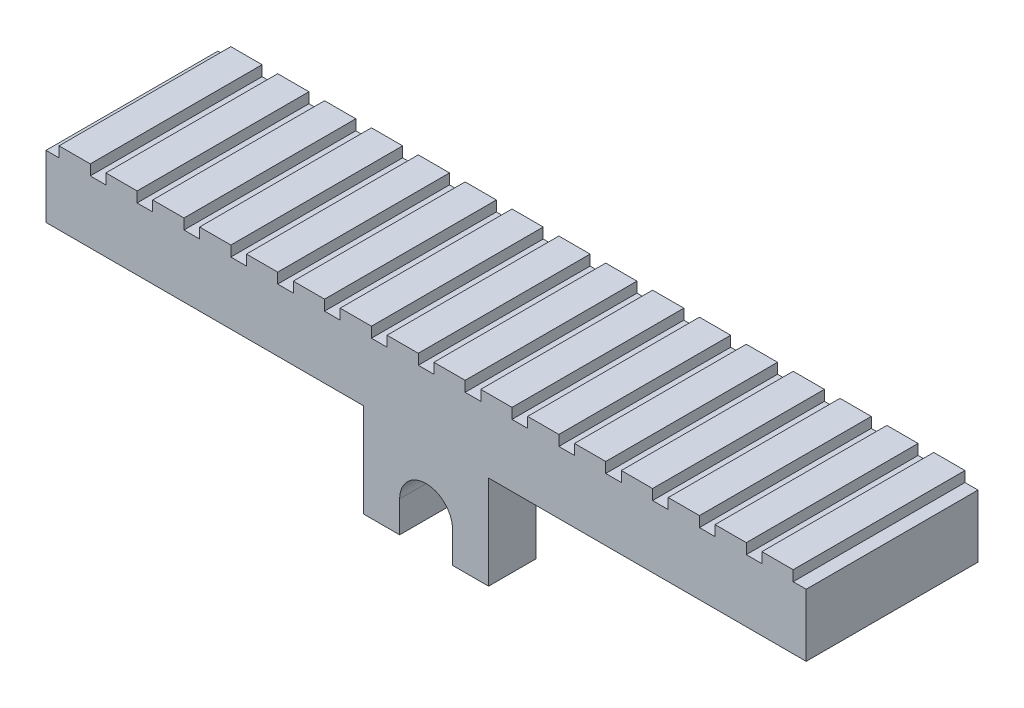
SolidWorks part; units mm, degrees
material "6061-T6 (SS)"
ref_plane "Front" through (0, 0, 0) normal (0, 0, 1) x (1, 0, 0)
ref_plane "Top" through (0, 0, 0) normal (0, 1, 0) x (1, 0, 0)
ref_plane "Right" through (0, 0, 0) normal (1, 0, 0) x (0, 0, -1)
sketch "Sketch4" plane through (0, 0, 0) normal (0, 1, 0) x (-1, 0, 0)
  line L2 (-36.5, 7.5) -> (36.5, 7.5)
  line L3 (-36.5, 7.5) -> (-36.5, -7.5)
  line L4 (-36.5, -7.5) -> (36.5, -7.5)
  line L5 (36.5, 7.5) -> (36.5, -7.5)
  point P1 (36.5, 0)
  point P2 (0, 7.5)
  dimension "D1" = 15
  dimension "D2" = 73
  dimension "D3" = 15
extrude "Boss-Extrude4" add sketch "Sketch4" against normal blind 6
sketch "Sketch15" plane through (0, 0, 0) normal (0, 1, 0) x (1, 0, 0)
  line L0 (0, 13.2788) -> (0, 21.5564) construction
  line L2 (0.75, 7.5) -> (3.75, 7.5)
  line L3 (0.75, 7.5) -> (0.75, -7.5)
  line L4 (0.75, -7.5) -> (3.75, -7.5)
  line L5 (3.75, 7.5) -> (3.75, -7.5)
  line L7 (5.25, 7.5) -> (8.25, 7.5)
  line L8 (5.25, 7.5) -> (5.25, -7.5)
  line L9 (5.25, -7.5) -> (8.25, -7.5)
  line L10 (8.25, 7.5) -> (8.25, -7.5)
  line L11 (9.75, 7.5) -> (12.75, 7.5)
  line L12 (9.75, 7.5) -> (9.75, -7.5)
  line L13 (9.75, -7.5) -> (12.75, -7.5)
  line L14 (12.75, 7.5) -> (12.75, -7.5)
  line L15 (14.25, 7.5) -> (17.25, 7.5)
  line L16 (14.25, 7.5) -> (14.25, -7.5)
  line L17 (14.25, -7.5) -> (17.25, -7.5)
  line L18 (17.25, 7.5) -> (17.25, -7.5)
  line L19 (18.75, 7.5) -> (21.75, 7.5)
  line L20 (18.75, 7.5) -> (18.75, -7.5)
  line L21 (18.75, -7.5) -> (21.75, -7.5)
  line L22 (21.75, 7.5) -> (21.75, -7.5)
  line L23 (23.25, 7.5) -> (26.25, 7.5)
  line L24 (23.25, 7.5) -> (23.25, -7.5)
  line L25 (23.25, -7.5) -> (26.25, -7.5)
  line L26 (26.25, 7.5) -> (26.25, -7.5)
  line L27 (27.75, 7.5) -> (30.75, 7.5)
  line L28 (27.75, 7.5) -> (27.75, -7.5)
  line L29 (27.75, -7.5) -> (30.75, -7.5)
  line L30 (30.75, 7.5) -> (30.75, -7.5)
  line L31 (32.25, 7.5) -> (35.25, 7.5)
  line L32 (32.25, 7.5) -> (32.25, -7.5)
  line L33 (32.25, -7.5) -> (35.25, -7.5)
  line L34 (35.25, 7.5) -> (35.25, -7.5)
  line L35 (-35.25, 7.5) -> (-35.25, -7.5)
  line L36 (-32.25, -7.5) -> (-35.25, -7.5)
  line L37 (-32.25, 7.5) -> (-32.25, -7.5)
  line L38 (-32.25, 7.5) -> (-35.25, 7.5)
  line L39 (-30.75, 7.5) -> (-30.75, -7.5)
  line L40 (-27.75, -7.5) -> (-30.75, -7.5)
  line L41 (-27.75, 7.5) -> (-27.75, -7.5)
  line L42 (-27.75, 7.5) -> (-30.75, 7.5)
  line L43 (-26.25, 7.5) -> (-26.25, -7.5)
  line L44 (-23.25, -7.5) -> (-26.25, -7.5)
  line L45 (-23.25, 7.5) -> (-23.25, -7.5)
  line L46 (-23.25, 7.5) -> (-26.25, 7.5)
  line L47 (-21.75, 7.5) -> (-21.75, -7.5)
  line L48 (-18.75, -7.5) -> (-21.75, -7.5)
  line L49 (-18.75, 7.5) -> (-18.75, -7.5)
  line L50 (-18.75, 7.5) -> (-21.75, 7.5)
  line L51 (-17.25, 7.5) -> (-17.25, -7.5)
  line L52 (-14.25, -7.5) -> (-17.25, -7.5)
  line L53 (-14.25, 7.5) -> (-14.25, -7.5)
  line L54 (-14.25, 7.5) -> (-17.25, 7.5)
  line L55 (-12.75, 7.5) -> (-12.75, -7.5)
  line L56 (-9.75, -7.5) -> (-12.75, -7.5)
  line L57 (-9.75, 7.5) -> (-9.75, -7.5)
  line L58 (-9.75, 7.5) -> (-12.75, 7.5)
  line L59 (-8.25, 7.5) -> (-8.25, -7.5)
  line L60 (-5.25, -7.5) -> (-8.25, -7.5)
  line L61 (-5.25, 7.5) -> (-5.25, -7.5)
  line L62 (-5.25, 7.5) -> (-8.25, 7.5)
  line L63 (-3.75, 7.5) -> (-3.75, -7.5)
  line L64 (-0.75, -7.5) -> (-3.75, -7.5)
  line L65 (-0.75, 7.5) -> (-0.75, -7.5)
  line L66 (-0.75, 7.5) -> (-3.75, 7.5)
  line L67 (36.5, 7.5) -> (-36.5, 7.5) construction
  line L68 (-36.5, -7.5) -> (36.5, -7.5) construction
  point P11 (2.25, 7.5)
  point P12 (-33.75, 7.5)
  point P13 (-29.25, 7.5)
  point P18 (6.75, 7.5)
  point P23 (11.25, 7.5)
  point P28 (15.75, 7.5)
  point P33 (20.25, 7.5)
  point P38 (24.75, 7.5)
  point P43 (29.25, 7.5)
  point P48 (33.75, 7.5)
  point P49 (-24.75, 7.5)
  point P50 (-20.25, 7.5)
  point P51 (-15.75, 7.5)
  point P52 (-11.25, 7.5)
  point P53 (-6.75, 7.5)
  point P54 (-2.25, 7.5)
  dimension "D1" = 3
  dimension "D2" = 4.5
  dimension "D4" = 4.5
  dimension "D3" = 8
extrude "Boss-Extrude6" add sketch "Sketch15" along normal blind 1
sketch "Sketch16" plane through (0, 0, 7.5) normal (0, 0, 1) x (1, 0, 0)
  line L68 (-35.25, 0) -> (-36.5, 0)
  line L69 (-36.5, 0) -> (-36.5, -6)
  line L70 (-36.5, -6) -> (36.5, -6)
  line L71 (36.5, -6) -> (36.5, 0)
  line L72 (36.5, 0) -> (35.25, 0)
  line L73 (35.25, 0) -> (35.25, 1)
  line L74 (35.25, 1) -> (32.25, 1)
  line L75 (32.25, 1) -> (32.25, 0)
  line L76 (32.25, 0) -> (30.75, 0)
  line L77 (30.75, 0) -> (30.75, 1)
  line L78 (30.75, 1) -> (27.75, 1)
  line L79 (27.75, 1) -> (27.75, 0)
  line L80 (27.75, 0) -> (26.25, 0)
  line L81 (26.25, 0) -> (26.25, 1)
  line L82 (26.25, 1) -> (23.25, 1)
  line L83 (23.25, 1) -> (23.25, 0)
  line L84 (23.25, 0) -> (21.75, 0)
  line L85 (21.75, 0) -> (21.75, 1)
  line L86 (21.75, 1) -> (18.75, 1)
  line L87 (18.75, 1) -> (18.75, 0)
  line L88 (18.75, 0) -> (17.25, 0)
  line L89 (17.25, 0) -> (17.25, 1)
  line L90 (17.25, 1) -> (14.25, 1)
  line L91 (14.25, 1) -> (14.25, 0)
  line L92 (14.25, 0) -> (12.75, 0)
  line L93 (12.75, 0) -> (12.75, 1)
  line L94 (12.75, 1) -> (9.75, 1)
  line L95 (9.75, 1) -> (9.75, 0)
  line L96 (9.75, 0) -> (8.25, 0)
  line L97 (8.25, 0) -> (8.25, 1)
  line L98 (8.25, 1) -> (5.25, 1)
  line L99 (5.25, 1) -> (5.25, 0)
  line L100 (5.25, 0) -> (3.75, 0)
  line L101 (3.75, 0) -> (3.75, 1)
  line L102 (3.75, 1) -> (0.75, 1)
  line L103 (0.75, 1) -> (0.75, 0)
  line L104 (0.75, 0) -> (-0.75, 0)
  line L105 (-0.75, 0) -> (-0.75, 1)
  line L106 (-0.75, 1) -> (-3.75, 1)
  line L107 (-3.75, 1) -> (-3.75, 0)
  line L108 (-3.75, 0) -> (-5.25, 0)
  line L109 (-5.25, 0) -> (-5.25, 1)
  line L110 (-5.25, 1) -> (-8.25, 1)
  line L111 (-8.25, 1) -> (-8.25, 0)
  line L112 (-8.25, 0) -> (-9.75, 0)
  line L113 (-9.75, 0) -> (-9.75, 1)
  line L114 (-9.75, 1) -> (-12.75, 1)
  line L115 (-12.75, 1) -> (-12.75, 0)
  line L116 (-12.75, 0) -> (-14.25, 0)
  line L117 (-14.25, 0) -> (-14.25, 1)
  line L118 (-14.25, 1) -> (-17.25, 1)
  line L119 (-17.25, 1) -> (-17.25, 0)
  line L120 (-17.25, 0) -> (-18.75, 0)
  line L121 (-18.75, 0) -> (-18.75, 1)
  line L122 (-18.75, 1) -> (-21.75, 1)
  line L123 (-21.75, 1) -> (-21.75, 0)
  line L124 (-21.75, 0) -> (-23.25, 0)
  line L125 (-23.25, 0) -> (-23.25, 1)
  line L126 (-23.25, 1) -> (-26.25, 1)
  line L127 (-26.25, 1) -> (-26.25, 0)
  line L128 (-26.25, 0) -> (-27.75, 0)
  line L129 (-27.75, 0) -> (-27.75, 1)
  line L130 (-27.75, 1) -> (-30.75, 1)
  line L131 (-30.75, 1) -> (-30.75, 0)
  line L132 (-30.75, 0) -> (-32.25, 0)
  line L133 (-32.25, 0) -> (-32.25, 1)
  line L134 (-32.25, 1) -> (-35.25, 1)
  line L135 (-35.25, 1) -> (-35.25, 0)
  line L136 (-35.25, 0) -> (-36.5, 0)
  line L137 (-36.5, 0) -> (-36.5, -6)
  line L138 (-36.5, -6) -> (36.5, -6)
  line L139 (36.5, -6) -> (36.5, 0)
  line L140 (36.5, 0) -> (35.25, 0)
  line L141 (35.25, 0) -> (35.25, 1)
  line L142 (35.25, 1) -> (32.25, 1)
  line L143 (32.25, 1) -> (32.25, 0)
  line L144 (32.25, 0) -> (30.75, 0)
  line L145 (30.75, 0) -> (30.75, 1)
  line L146 (30.75, 1) -> (27.75, 1)
  line L147 (27.75, 1) -> (27.75, 0)
  line L148 (27.75, 0) -> (26.25, 0)
  line L149 (26.25, 0) -> (26.25, 1)
  line L150 (26.25, 1) -> (23.25, 1)
  line L151 (23.25, 1) -> (23.25, 0)
  line L152 (23.25, 0) -> (21.75, 0)
  line L153 (21.75, 0) -> (21.75, 1)
  line L154 (21.75, 1) -> (18.75, 1)
  line L155 (18.75, 1) -> (18.75, 0)
  line L156 (18.75, 0) -> (17.25, 0)
  line L157 (17.25, 0) -> (17.25, 1)
  line L158 (17.25, 1) -> (14.25, 1)
  line L159 (14.25, 1) -> (14.25, 0)
  line L160 (14.25, 0) -> (12.75, 0)
  line L161 (12.75, 0) -> (12.75, 1)
  line L162 (12.75, 1) -> (9.75, 1)
  line L163 (9.75, 1) -> (9.75, 0)
  line L164 (9.75, 0) -> (8.25, 0)
  line L165 (8.25, 0) -> (8.25, 1)
  line L166 (8.25, 1) -> (5.25, 1)
  line L167 (5.25, 1) -> (5.25, 0)
  line L168 (5.25, 0) -> (3.75, 0)
  line L169 (3.75, 0) -> (3.75, 1)
  line L170 (3.75, 1) -> (0.75, 1)
  line L171 (0.75, 1) -> (0.75, 0)
  line L172 (0.75, 0) -> (-0.75, 0)
  line L173 (-0.75, 0) -> (-0.75, 1)
  line L174 (-0.75, 1) -> (-3.75, 1)
  line L175 (-3.75, 1) -> (-3.75, 0)
  line L176 (-3.75, 0) -> (-5.25, 0)
  line L177 (-5.25, 0) -> (-5.25, 1)
  line L178 (-5.25, 1) -> (-8.25, 1)
  line L179 (-8.25, 1) -> (-8.25, 0)
  line L180 (-8.25, 0) -> (-9.75, 0)
  line L181 (-9.75, 0) -> (-9.75, 1)
  line L182 (-9.75, 1) -> (-12.75, 1)
  line L183 (-12.75, 1) -> (-12.75, 0)
  line L184 (-12.75, 0) -> (-14.25, 0)
  line L185 (-14.25, 0) -> (-14.25, 1)
  line L186 (-14.25, 1) -> (-17.25, 1)
  line L187 (-17.25, 1) -> (-17.25, 0)
  line L188 (-17.25, 0) -> (-18.75, 0)
  line L189 (-18.75, 0) -> (-18.75, 1)
  line L190 (-18.75, 1) -> (-21.75, 1)
  line L191 (-21.75, 1) -> (-21.75, 0)
  line L192 (-21.75, 0) -> (-23.25, 0)
  line L193 (-23.25, 0) -> (-23.25, 1)
  line L194 (-23.25, 1) -> (-26.25, 1)
  line L195 (-26.25, 1) -> (-26.25, 0)
  line L196 (-26.25, 0) -> (-27.75, 0)
  line L197 (-27.75, 0) -> (-27.75, 1)
  line L198 (-27.75, 1) -> (-30.75, 1)
  line L199 (-30.75, 1) -> (-30.75, 0)
  line L200 (-30.75, 0) -> (-32.25, 0)
  line L201 (-32.25, 0) -> (-32.25, 1)
  line L202 (-32.25, 1) -> (-35.25, 1)
  line L203 (-35.25, 1) -> (-35.25, 0)
  dimension "D1" = 0
extrude "Boss-Extrude7" add sketch "Sketch16" along normal blind 1.5
sketch "Sketch21" plane through (0, 0, 9) normal (0, 0, 1) x (1, 0, 0)
  line L0 (0, -21.2656) -> (0, -26.6039) construction
  line L1 (-2.54, -12) -> (-2.54, -15)
  line L2 (-6, -6) -> (6, -6)
  line L3 (-6, -6) -> (-6, -15)
  line L4 (-6, -15) -> (-2.54, -15)
  line L5 (6, -6) -> (6, -15)
  line L6 (2.54, -12) -> (2.54, -15)
  line L7 (2.54, -15) -> (6, -15)
  line L10 (-36.5, -6) -> (36.5, -6) construction
  arc A0 (2.54, -12) -> (-2.54, -12) centre (0, -12) ccw
  point P6 (0, -6)
  dimension "D3" = 5.08
  dimension "D1" = 12
  dimension "D2" = 9
  dimension "D4" = 6
extrude "Boss-Extrude13" add sketch "Sketch21" against normal blind 7.715
sketch "Sketch22" plane through (0, -6, 0) normal (0, -1, 0) x (1, 0, 0)
  line L8 (-6, 1.285) -> (-6, 9) construction
  line L9 (-6, 7) -> (6, 7)
  line L10 (-6, 7) -> (-6, 3.285)
  line L11 (-6, 3.285) -> (6, 3.285)
  line L12 (6, 7) -> (6, 3.285)
  line L13 (6, 1.285) -> (6, 9) construction
  line L14 (-6, 9) -> (-2.54, 9) construction
  line L15 (-6, 1.285) -> (-2.54, 1.285) construction
  dimension "D1" = 2
  dimension "D3" = 2
extrude "Cut-Extrude2" cut sketch "Sketch22" along normal up to surface (9 mm away) up to face at (4.27, -15, 5.1425)
sketch "Sketch23" plane through (0, 0, 1.285) normal (0, 0, -1) x (-1, 0, 0)
  line L7 (6, -15) -> (6, -6)
  line L8 (6, -6) -> (-6, -6)
  line L9 (-6, -6) -> (-6, -15)
  line L10 (-6, -15) -> (-2.54, -15)
  line L11 (-2.54, -15) -> (-2.54, -12)
  line L12 (2.54, -12) -> (2.54, -15)
  line L13 (2.54, -15) -> (6, -15)
  line L14 (6, -15) -> (6, -6)
  line L15 (6, -6) -> (-6, -6)
  line L16 (-6, -6) -> (-6, -15)
  line L17 (-6, -15) -> (-2.54, -15)
  line L18 (-2.54, -15) -> (-2.54, -12)
  line L19 (2.54, -12) -> (2.54, -15)
  line L20 (2.54, -15) -> (6, -15)
  arc A1 (2.54, -12) -> (-2.54, -12) centre (0, -12) ccw
  arc A2 (2.54, -12) -> (-2.54, -12) centre (0, -12) ccw
  dimension "D1" = 0
extrude "Cut-Extrude3" cut sketch "Sketch23" against normal up to next
sketch "Sketch24" plane through (0, 0, 7) normal (0, 0, -1) x (-1, 0, 0)
  line L7 (2.54, -12) -> (2.54, -15)
  line L8 (2.54, -15) -> (6, -15)
  line L9 (6, -15) -> (6, -6)
  line L10 (6, -6) -> (-6, -6)
  line L11 (-6, -6) -> (-6, -15)
  line L12 (-6, -15) -> (-2.54, -15)
  line L13 (-2.54, -15) -> (-2.54, -12)
  line L14 (2.54, -12) -> (2.54, -15)
  line L15 (2.54, -15) -> (6, -15)
  line L16 (6, -15) -> (6, -6)
  line L17 (6, -6) -> (-6, -6)
  line L18 (-6, -6) -> (-6, -15)
  line L19 (-6, -15) -> (-2.54, -15)
  line L20 (-2.54, -15) -> (-2.54, -12)
  arc A1 (2.54, -12) -> (-2.54, -12) centre (0, -12) ccw
  arc A2 (2.54, -12) -> (-2.54, -12) centre (0, -12) ccw
  dimension "D1" = 0
extrude "Boss-Extrude14" add sketch "Sketch24" along normal blind 2.54
